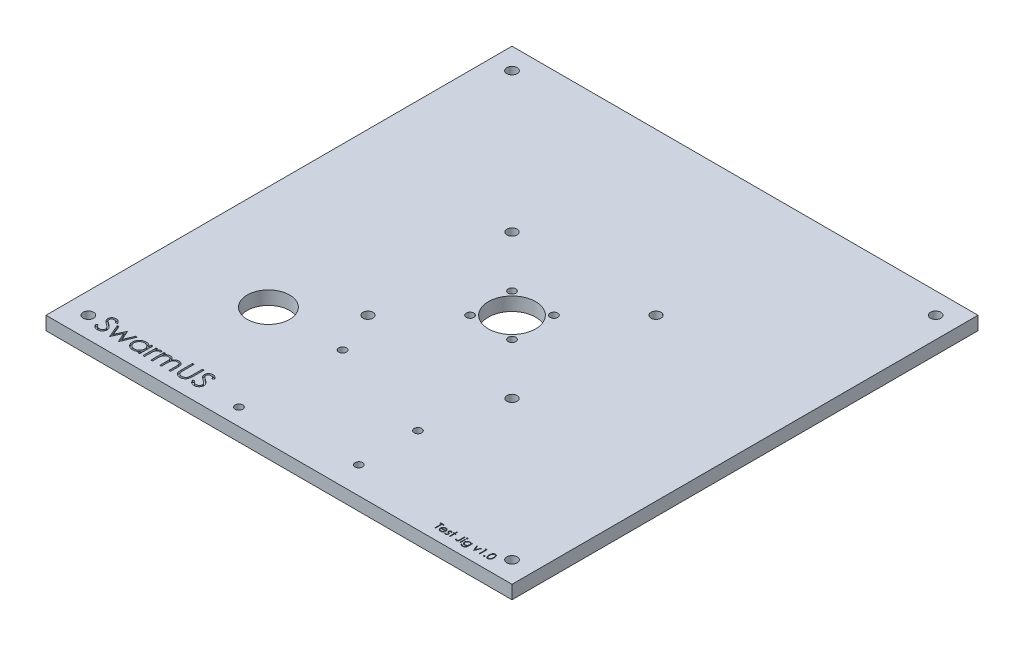
SolidWorks part; units mm, degrees
material "Pin"
ref_plane "Plan de face" through (0, 0, 0) normal (0, 0, 1) x (1, 0, 0)
ref_plane "Plan de dessus" through (0, 0, 0) normal (0, 1, 0) x (1, 0, 0)
ref_plane "Plan de droite" through (0, 0, 0) normal (1, 0, 0) x (0, 0, -1)
sketch "Esquisse1" plane through (0, 0, 0) normal (0, 1, 0) x (1, 0, 0)
  line L1 (-110, 110) -> (110, 110)
  line L2 (-110, 110) -> (-110, -110)
  line L3 (-110, -110) -> (110, -110)
  line L4 (110, 110) -> (110, -110)
  point P4 (0, 110)
  point P6 (110, 0)
  dimension "D1" = 220
  dimension "D2" = 220
extrude "Boss.-Extru.1" add sketch "Esquisse1" along normal blind 6.35
sketch "Esquisse2" plane through (0, 6.35, 0) normal (0, 1, 0) x (1, 0, 0)
  circle A0 centre (0, 0) radius 11.15
  dimension "D1" = 22.3
extrude "Enlèv. mat.-Extru.1" cut sketch "Esquisse2" against normal up to surface (6.35 mm away) up to face at (0, 0, 0)
sketch "Esquisse3" plane through (0, 6.35, 0) normal (0, 1, 0) x (1, 0, 0)
  circle A0 centre (0, 0) radius 14 construction
  dimension "D1" = 28
hole_wizard "Dégagement M31" positions "Esquisse4" profile "Esquisse5" hole size "M3" standard "Ansi Metric" end condition through all
sketch "Esquisse4" plane through (0, 6.35, 0) normal (0, 1, 0) x (1, 0, 0)
  line L0 (0, 0) -> (0, 14) construction
  line L2 (0, 0) -> (-9.8995, 9.8995) construction
  circle A0 centre (0, 0) radius 14 construction
  point P0 (-9.8995, 9.8995)
  dimension "D1" = 45
sketch "Esquisse5" plane through (-9.8995, 6.35, -9.8995) normal (1, 0, 0) x (0, 0, 1)
  line L0 (0, 0) -> (0, 6.35)
  line L1 (0, 6.35) -> (1.8, 6.35)
  line L2 (1.8, 6.35) -> (1.8, 0)
  line L5 (1.8, 0) -> (0, 0)
  line L11 (0, -6.35) -> (0, 107.95) construction
  dimension "Diamètre du perçage jusqu'au prochain" = 3.6
  dimension "Profondeur du perçage jusqu'au prochain" = 6.35
hole_wizard "Dégagement M41" positions "Esquisse6" profile "Esquisse7" hole size "M4" standard "Ansi Metric" end condition through all
sketch "Esquisse6" plane through (0, 6.35, 0) normal (0, 1, 0) x (1, 0, 0)
  line L1 (0, 0) -> (-9.8995, 9.8995) construction
  point P0 (-34, 34)
  dimension "D1" = 34
sketch "Esquisse7" plane through (-34, 6.35, -34) normal (1, 0, 0) x (0, 0, 1)
  line L0 (0, 0) -> (0, 6.35)
  line L1 (0, 6.35) -> (2.4, 6.35)
  line L2 (2.4, 6.35) -> (2.4, 0)
  line L5 (2.4, 0) -> (0, 0)
  line L11 (0, -6.35) -> (0, 107.95) construction
  dimension "Diamètre du perçage jusqu'au prochain" = 4.8
  dimension "Profondeur du perçage jusqu'au prochain" = 6.35
pattern_circular "Répétition circulaire1" count 4 over 360 about axis through (0, 0, 0) along (0, 1, 0) of "Dégagement M31", "Dégagement M41"
hole_wizard "#8 Clearance Hole1" positions "Sketch1" profile "Sketch2" hole size "#8" standard "ANSI Inch"
sketch "Sketch1" plane through (0, 6.35, 0) normal (0, 1, 0) x (1, 0, 0)
  line L0 (-100, 100) -> (100, -100) construction
  line L2 (100, 100) -> (-100, -100) construction
  line L3 (110, 110) -> (-110, 110) construction
  point P0 (-100, 100)
  point P2 (100, 100)
  point P4 (100, -100)
  point P6 (-100, -100)
  point P22 (0, 0)
  point P23 (0, 0)
  dimension "D1" = 10
sketch "Sketch2" plane through (-100, 6.35, -100) normal (1, 0, 0) x (0, 0, 1)
  line L0 (0, 0) -> (0, 7.8256)
  line L1 (0, 7.8256) -> (2.4574, 6.349)
  line L2 (2.4574, 6.349) -> (2.4574, 0)
  line L5 (2.4574, 0) -> (0, 0)
  line L10 (0, 7.8256) -> (-2.4575, 6.349) construction
  line L11 (0, -6.35) -> (0, 107.95) construction
  dimension "Hole Dia." = 4.9149
  dimension "Hole Depth" = 6.349
  dimension "Drill Angle" = 118
sketch "uno_footprint" plane through (0, 6.35, 0) normal (0, 1, 0) x (1, 0, 0)
  line L0 (-110, -110) -> (110, -110) construction
  line L1 (110, -110) -> (110, 110) construction
  circle A0 centre (-25.8, -54.2) radius 1.6 construction
  circle A2 centre (25, -69.4) radius 1.6 construction
  circle A3 centre (25, -97.3) radius 1.6 construction
  circle A4 centre (-26.9, -102) radius 1.6 construction
  dimension "D1" = 1.1
  dimension "D7" = 3.2
  dimension "D2" = 50.8
  dimension "D3" = 15.2
  dimension "D4" = 27.9
  dimension "D5" = 4.7
  dimension "D6" = 51.9
  dimension "D8" = 8
  dimension "D9" = 85
hole_wizard "M3 Clearance Hole1" positions "Sketch4" profile "Sketch5" hole size "M3" standard "ANSI Metric"
sketch "Sketch4" plane through (0, 6.35, 0) normal (0, 1, 0) x (1, 0, 0)
  point P0 (25, -69.4)
  point P3 (-25.8, -54.2)
  point P6 (-26.9, -102)
  point P9 (25, -97.3)
sketch "Sketch5" plane through (25, 6.35, 69.4) normal (1, 0, 0) x (0, 0, 1)
  line L0 (0, 0) -> (0, 7.4305)
  line L1 (0, 7.4305) -> (1.8, 6.349)
  line L2 (1.8, 6.349) -> (1.8, 0)
  line L5 (1.8, 0) -> (0, 0)
  line L10 (0, 7.4305) -> (-1.8, 6.349) construction
  line L11 (0, -6.35) -> (0, 107.95) construction
  dimension "Hole Dia." = 3.6
  dimension "Hole Depth" = 6.349
  dimension "Drill Angle" = 118
sketch "Sketch6" plane through (0, 6.35, 0) normal (0, 1, 0) x (1, 0, 0)
  circle A0 centre (-60.8, -54.2) radius 10
  dimension "D1" = 20
  dimension "D2" = 35
extrude "Cut-Extrude1" cut sketch "Sketch6" against normal up to surface (6.35 mm away) up to face at (25, 0, 71.2)
sketch "Sketch7" plane through (0, 6.35, 0) normal (0, 1, 0) x (1, 0, 0)
  text T1 "Test Jig v1.0" font "Century Gothic" height 3.5
sketch "Sketch9" plane through (0, 6.35, 0) normal (0, 1, 0) x (1, 0, 0)
  text T0 "SwarmUS" font "Century Gothic" height 8.5
extrude "Cut-Extrude2" cut sketch "Sketch9" against normal blind 1
extrude "Cut-Extrude3" cut sketch "Sketch7" against normal blind 1
